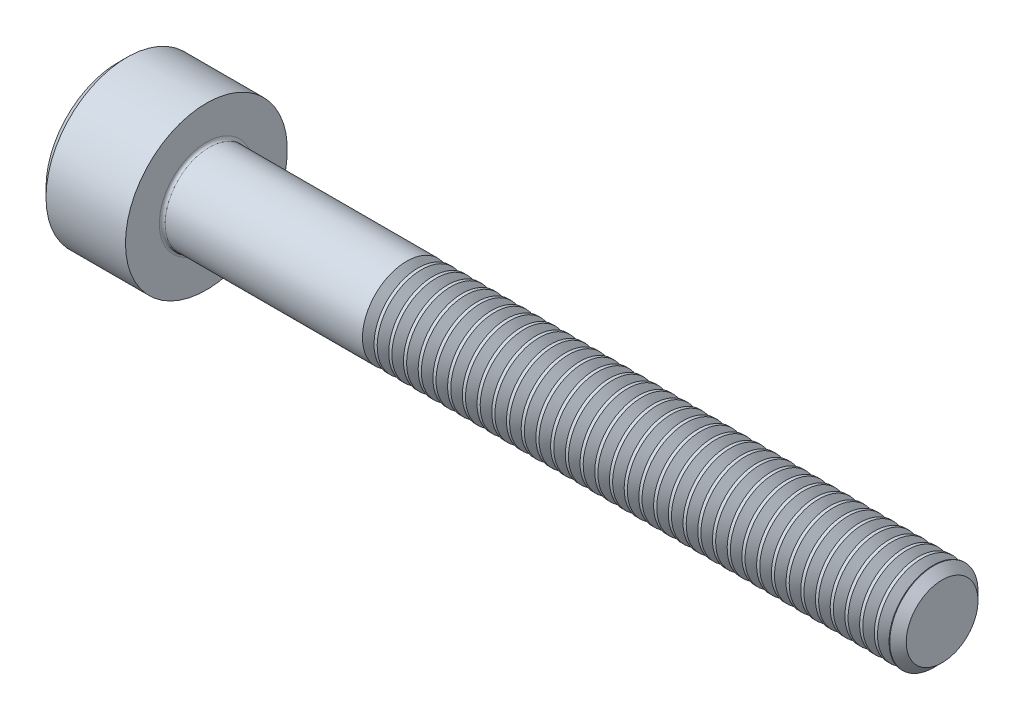
SolidWorks part; units mm, degrees
revolve "Base-Revolve" add sketch "BodySke"
sketch "BodySke" plane through (0, 0, 0) normal (0, 0, 1) x (1, 0, 0)
  line L0 (0, 0) -> (0, 2.45)
  line L1 (0.3, 2.75) -> (3, 2.75)
  line L2 (3, 2.75) -> (3, 1.5)
  line L3 (3, 1.5) -> (27.7195, 1.5)
  line L4 (28, 1.2195) -> (28, 0)
  line L5 (28, 0) -> (0, 0)
  line L6 (-31.75, 0) -> (127, 0) construction
  line L7 (0, 2.45) -> (0.3, 2.75)
  line L8 (28, 1.2195) -> (27.7195, 1.5)
  line L9 (0, -2.45) -> (0.3, -2.75) construction
  line L10 (28, -1.2195) -> (27.7195, -1.5) construction
  line L11 (3.5, 9.525) -> (3.5, 3.175) construction
  line L12 (10, 9.525) -> (10, 3.175) construction
  line L13 (-22, 9.525) -> (-22, 3.175) construction
  dimension "Diameter" = 3
  dimension "Head_ht" = 3
  dimension "Length" = 25
  dimension "Body_ch_ang" = 45
  dimension "Head_dia" = 5.5
  dimension "Head_ch_ang" = 45
  dimension "Minor_dia" = 2.439
  dimension "Advance" = 0.5
  dimension "Thread_nom" = 18
  dimension "Thread_length" = 50
  dimension "Head_ch_ht" = 0.3
cosmetic thread "ThreadCosmetic" [suppressed]
fillet "Fillet1" radius 0.1 1 edges at (3, 0, 1.5)
ref_plane "Plane1" through (0, 0, 0) normal (0, 0, 1) x (1, 0, 0)
ref_plane "Plane2" through (0, 0, 0) normal (0, 1, 0) x (1, 0, 0)
ref_plane "Plane3" through (0, 0, 0) normal (1, 0, 0) x (0, 0, -1)
sketch "Sketch2" plane through (0, 0, 0) normal (0, 0, 1) x (1, 0, 0)
  line L0 (0, 1.28) -> (1.3, 1.28)
  line L1 (1.3, 1.28) -> (2.039, 0)
  line L2 (-31.75, 0) -> (127, 0) construction
  line L3 (2.039, 0) -> (0, 0)
  line L4 (0, 0) -> (0, 1.28)
  line L5 (0, 2.45) -> (0, -2.45) construction
  line L6 (0, 0) -> (47.625, 0) construction
  line L7 (3, -2.75) -> (3, 2.75) construction
  dimension "D1" = 1.28
  dimension "D2" = 60
revolve "Hex-PreBroach" cut sketch "Sketch2" angle 360 about L6
sketch "Sketch3" plane through (0, 0, 0) normal (-1, 0, 0) x (0, 0.5, 0.866)
  line L0 (0.739, 1.28) -> (-0.739, 1.28)
  line L1 (-0.739, 1.28) -> (-1.478, 0)
  line L2 (0.739, 1.28) -> (1.478, 0)
  line L3 (0.739, -1.28) -> (1.478, 0)
  line L4 (0.739, -1.28) -> (-0.739, -1.28)
  line L5 (-0.739, -1.28) -> (-1.478, 0)
  dimension "D1" = 1.28
  dimension "D2" = 1.28
  dimension "Hex_size" = 2.56
extrude "Hex" cut sketch "Sketch3" against normal blind 1.3
sketch "Sketch4" plane through (0, 0, 0) normal (-1, 0, 0) x (0, 0, 1)
  line L0 (0, 0) -> (1.4605, 0)
  line L1 (0, 0) -> (6.1484, 3.5498) construction
  line L2 (0, 0) -> (0.7302, 1.2648)
  line L3 (1.2009, 0.3267) -> (1.3933, 0.4378)
  line L4 (0.8834, 0.8767) -> (1.0758, 0.9877)
  arc A0 (1.2009, 0.3267) -> (0.8834, 0.8767) centre (0, 0) ccw
  arc A1 (1.4605, 0) -> (1.3933, 0.4378) centre (0, 0) ccw
  arc A2 (0.7302, 1.2648) -> (1.0758, 0.9877) centre (0, 0) cw
  dimension "D1" = 30
  dimension "D2" = 60
  dimension "Spline_p_dim" = 0.635
  dimension "D3" = 0.3175
extrude "Spline" [suppressed] cut sketch "Sketch4" against normal blind 1.3
pattern_circular "CirPattern1" [suppressed] count 6 every 60
sketch "Sketch5" plane through (0, 0, 0) normal (0, 0, 1) x (1, 0, 0)
  line L0 (-31.75, 0) -> (127, 0) construction
  line L2 (0, 2.45) -> (0, -2.45) construction
  circle A0 centre (1.2, 0) radius 0.475
  dimension "Drilled_hole_dia" = 0.95
  dimension "Drilled_hole_loc" = 1.2
extrude "Hole" [suppressed] cut sketch "Sketch5" against normal through all and the other way through all
pattern_circular "Drilled-4" [suppressed] count 2 every 60
pattern_circular "Drilled-6" [suppressed] count 3 every 60
sketch "ThdSchSke" plane through (0, 0, 0) normal (0, 0, 1) x (1, 0, 0)
  line L0 (10, -1.2195) -> (9.8036, -1.5)
  line L1 (10, -1.2195) -> (10.1964, -1.5)
  line L2 (10.1964, -1.5) -> (10.1964, -1.875)
  line L3 (-3.175, 0) -> (5.1513, 0) construction
  line L5 (10.1964, -1.875) -> (9.8036, -1.875)
  line L6 (9.8036, -1.875) -> (9.8036, -1.5)
  line L7 (0, 2.45) -> (0, -2.45) construction
  dimension "Thread_minor" = 2.439
  dimension "Diameter" = 3
  dimension "Start" = 10
revolve "ThreadSchematic" cut sketch "ThdSchSke" angle 360 about L3
pattern_linear "ThdSchPat" count 36 spacing 0.5 along (1, 0, 0) of "ThreadSchematic"
equation "\"D2@Sketch3\" = \"Hex_size@Sketch3\" / 2"
equation "\"D1@Sketch3\" = \"Hex_size@Sketch3\" / 2"
equation "\"D1@Sketch2\" = \"Hex_size@Sketch3\" / 2"
equation "\"D3@Sketch4\" = \"Spline_p_dim@Sketch4\" / 2"
equation "\"Thread_minor@ThreadCosmetic\"  =  \"Minor_dia@BodySke\""
equation "\"D2@CirPattern1\" = 360 / \"Num_teeth@CirPattern1\""
equation "\"Wall_thickness@Sketch2\" = \"Head_ht@BodySke\" - \"Key_eng@Hex\""
equation "\"Thread_length@ThreadCosmetic\" = ((sgn( (\"Length@BodySke\" - \"Advance@BodySke\" ) - \"Thread_nom@BodySke\" )-1)*( (\"Length@BodySke\" - \"Advance@BodySke\" ) - \"Thread_nom@BodySke\" ))/-2+ \"Thread_nom@BodySke\""
equation "\"Thread_minor@ThdSchSke\" = \"Minor_dia@BodySke\""
equation "\"Diameter@ThdSchSke\" = \"Diameter@BodySke\""
equation "\"Overcut@ThdSchSke\" = \"Diameter@BodySke\" * 1.25"
equation "\"Start@ThdSchSke\" = \"Head_ht@BodySke\" + \"Length@BodySke\" - \"Thread_length@ThreadCosmetic\"  '---Non-countersunk---"
equation "\"Num_threads@ThdSchPat\" = int( \"Thread_length@ThreadCosmetic\" / \"Advance@BodySke\" + 0.999 )  + 1"
equation "\"Advance@ThdSchPat\" = \"Thread_length@ThreadCosmetic\" /  (\"Num_threads@ThdSchPat\" - 1) 'relax it"
equation "\"Num_threads@ThdSchPat\" = \"Num_threads@ThdSchPat\" - sgn( \"Num_threads@ThdSchPat\" - 1) '---chamfered tips only---"
